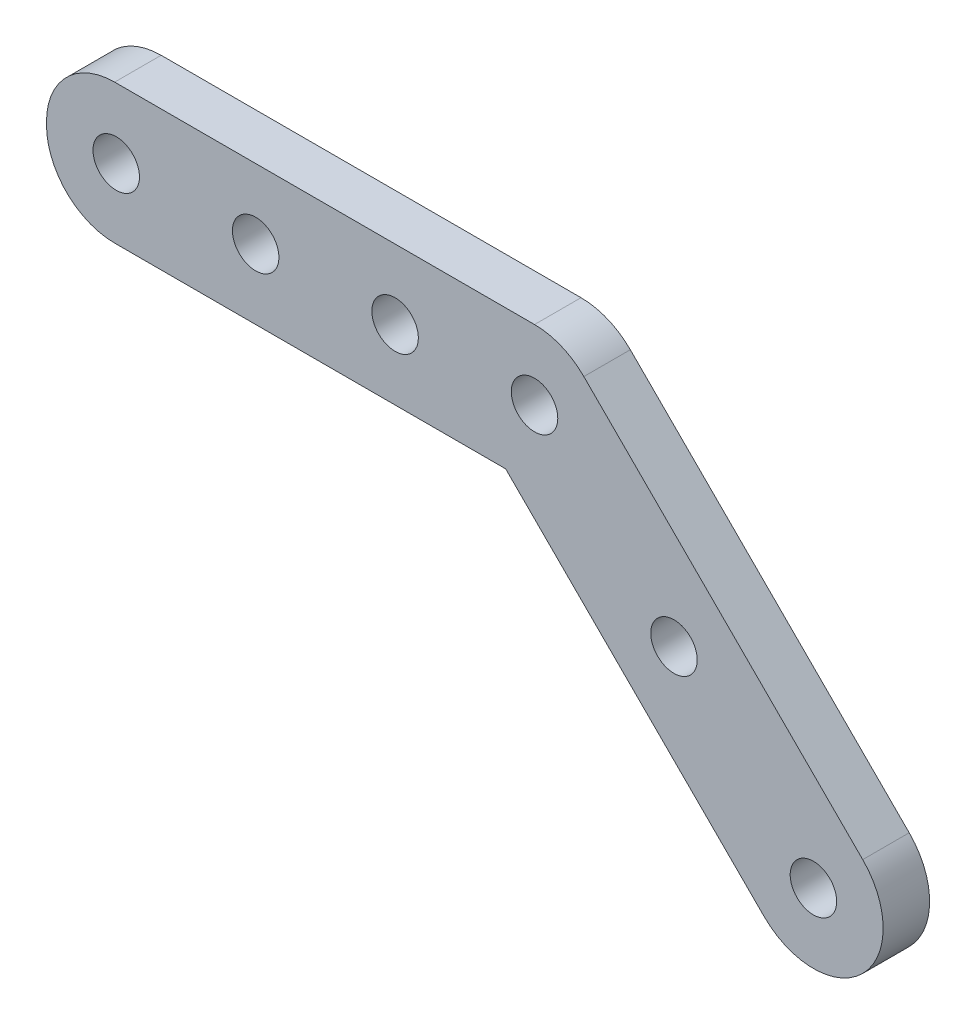
SolidWorks part; units mm, degrees
ref_plane "Alzado" through (0, 0, 0) normal (0, 0, 1) x (1, 0, 0)
ref_plane "Planta" through (0, 0, 0) normal (0, 1, 0) x (1, 0, 0)
ref_plane "Vista lateral" through (0, 0, 0) normal (1, 0, 0) x (0, 0, -1)
sketch "Model" plane through (0, 0, 0) normal (0, 0, 1) x (1, 0, 0)
  line L0 (145.8375, 264.0563) -> (162.5195, 247.3743)
  line L1 (168.8834, 253.7382) -> (150.8834, 271.7382)
  line L2 (147.7015, 273.0563) -> (120.6015, 273.0563)
  line L3 (116.2015, 268.6563) -> (116.2015, 268.4563)
  line L4 (120.6015, 264.0563) -> (145.8375, 264.0563)
  circle A0 centre (129.7015, 268.5563) radius 1.5
  circle A1 centre (138.7015, 268.5563) radius 1.5
  circle A2 centre (120.7015, 268.5563) radius 1.5
  circle A3 centre (147.7015, 268.5563) radius 1.5
  circle A4 centre (165.7015, 250.5563) radius 1.5
  circle A5 centre (156.7015, 259.5563) radius 1.5
  arc A6 (162.5195, 247.3743) -> (168.8834, 253.7382) centre (165.7015, 250.5563) ccw
  arc A7 (150.8834, 271.7382) -> (147.7015, 273.0563) centre (147.7015, 268.5563) ccw
  arc A8 (120.6015, 273.0563) -> (116.2015, 268.6563) centre (120.6015, 268.6563) ccw
  arc A9 (116.2015, 268.4563) -> (120.6015, 264.0563) centre (120.6015, 268.4563) ccw
extrude "Saliente-Extruir1" add sketch "Model" along normal blind 3
